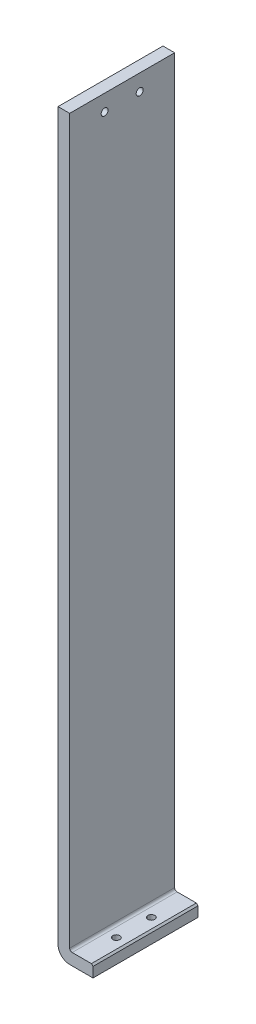
SolidWorks part; units mm, degrees
material "Acrylic (Medium-high impact)"
ref_plane "Front Plane" through (0, 0, 0) normal (0, 0, 1) x (1, 0, 0)
ref_plane "Top Plane" through (0, 0, 0) normal (0, 1, 0) x (1, 0, 0)
ref_plane "Right Plane" through (0, 0, 0) normal (1, 0, 0) x (0, 0, -1)
sketch "Sketch1" plane through (0, 0, 0) normal (0, 0, 1) x (1, 0, 0)
  line L0 (2.5, -163.5607) -> (12.5, -163.5607)
  line L2 (-2.5, -158.5607) -> (-2.5, 152.5)
  line L3 (-2.5, 152.5) -> (2.5, 152.5)
  line L4 (2.5, -157.5) -> (2.5, 152.5)
  line L7 (12.5, -163.5607) -> (12.5, -158.5607)
  line L8 (12.5, -158.5607) -> (3.5607, -158.5607)
  arc A0 (-2.5, -158.5607) -> (2.5, -163.5607) centre (2.5, -158.5607) ccw
  arc A1 (2.5, -157.5) -> (3.5607, -158.5607) centre (3.5607, -157.5) ccw
  point P0 (0, 0)
  point P2 (0, 0)
  point P12 (0, 0)
  point P14 (0, 0)
extrude "Boss-Extrude1" add sketch "Sketch1" along normal blind 45
sketch "Sketch2" plane through (0, 0, 0) normal (0, 1, 0) x (1, 0, 0)
  line L0 (2.5, 0) -> (12.5, 0) construction
  line L1 (7.5, 0) -> (7.5, -15) construction
  line L2 (2.5, -45) -> (12.5, -45) construction
  line L3 (2.5, -45) -> (2.5, 0) construction
  line L4 (2.5, -45) -> (2.5, 0) construction
  line L5 (12.5, -45) -> (3.5607, -45) construction
  line L6 (7.5, -45) -> (7.5, -30) construction
  circle A0 centre (7.5, -15) radius 1.5
  circle A1 centre (7.5, -30) radius 1.5
extrude "Cut-Extrude1" cut sketch "Sketch2" against normal blind 10 from surface at -158.5607 starting at face at (8.0303, -158.5607, 22.5)
sketch "Sketch3" plane through (0, 0, 0) normal (1, 0, 0) x (0, 0, -1)
  line L0 (-22.5, 152.5) -> (-22.5, 145.5) construction
  line L1 (-45, 152.5) -> (0, 152.5) construction
  line L2 (0, 145.5) -> (-15, 145.5) construction
  line L3 (0, -157.5) -> (0, 152.5) construction
  line L4 (-45, 145.5) -> (-30, 145.5) construction
  line L5 (-45, -157.5) -> (-45, 152.5) construction
  circle A0 centre (-15, 145.5) radius 1.5
  circle A1 centre (-30, 145.5) radius 1.5
extrude "Cut-Extrude2" cut sketch "Sketch3" against normal blind 10 and the other way blind 10
chamfer "Chamfer1" distance 0.7 angle 45 1 edges at (12.5, -158.5607, 22.5)
